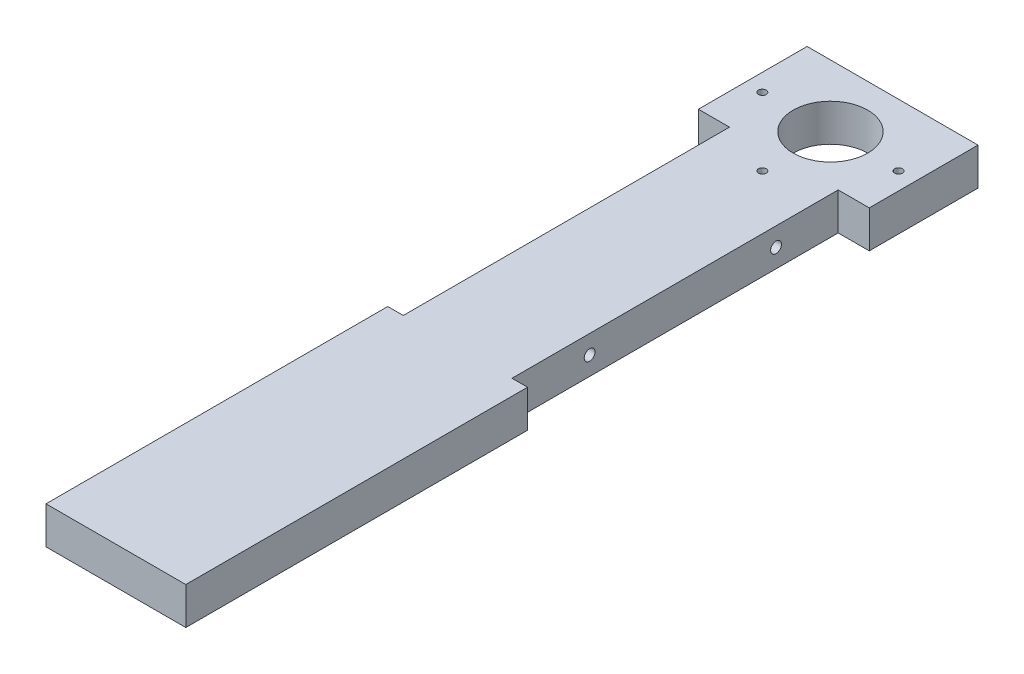
SolidWorks part; units mm, degrees
ref_plane "Front Plane" through (0, 0, 0) normal (0, 0, 1) x (1, 0, 0)
ref_plane "Top Plane" through (0, 0, 0) normal (0, 1, 0) x (1, 0, 0)
ref_plane "Right Plane" through (0, 0, 0) normal (1, 0, 0) x (0, 0, -1)
sketch "Sketch1" plane through (0, 0, 0) normal (0, 1, 0) x (1, 0, 0)
  line L1 (-22.5, 125) -> (22.5, 125)
  line L2 (-22.5, 125) -> (-22.5, -125)
  line L3 (-22.5, -125) -> (22.5, -125)
  line L4 (22.5, 125) -> (22.5, -125)
  line L5 (-22.5, 125) -> (22.5, -125) construction
  line L6 (-22.5, -125) -> (22.5, 125) construction
  point P0 (0, 0)
  dimension "D1" = 250
  dimension "D2" = 45
extrude "Boss-Extrude1" add sketch "Sketch1" along normal blind 12
sketch "Sketch2" plane through (0, 12, 0) normal (0, 1, 0) x (1, 0, 0)
  line L0 (22.5, 125) -> (22.5, 90) construction
  line L1 (22.5, -125) -> (22.5, 125) construction
  line L2 (0, -6.6) -> (0, 6.6) construction
  line L3 (22.5, 90) -> (17.5, 90)
  line L4 (22.5, 90) -> (22.5, -15)
  line L5 (22.5, -15) -> (17.5, -15)
  line L6 (17.5, 90) -> (17.5, -15)
  line L7 (-22.5, -15) -> (-17.5, -15)
  line L8 (-17.5, 90) -> (-17.5, -15)
  line L9 (-22.5, 90) -> (-17.5, 90)
  line L10 (-22.5, 90) -> (-22.5, -15)
  dimension "D2" = 105
  dimension "D1" = 35
  dimension "D3" = 5
extrude "Cut-Extrude1" cut sketch "Sketch2" against normal blind 12
sketch "Sketch3" plane through (17.5, 0, 0) normal (1, 0, 0) x (0, 0, -1)
  line L0 (90, 6) -> (70, 6) construction
  line L1 (90, 0) -> (90, 12) construction
  line L2 (70, 6) -> (10, 6) construction
  circle A0 centre (10, 6) radius 1.75
  circle A1 centre (70, 6) radius 1.75
  dimension "D3" = 3.5
  dimension "D4" = 3.5
  dimension "D1" = 20
  dimension "D2" = 60
extrude "Cut-Extrude2" cut sketch "Sketch3" against normal blind 35
sketch "Sketch5" plane through (0, 12, 0) normal (0, 1, 0) x (1, 0, 0)
  line L1 (22.5, 125) -> (27.5, 125)
  line L2 (22.5, 125) -> (22.5, 90)
  line L3 (22.5, 90) -> (27.5, 90)
  line L4 (27.5, 125) -> (27.5, 90)
  line L5 (-22.5, 125) -> (-27.5, 125)
  line L6 (-22.5, 125) -> (-22.5, 90)
  line L7 (-22.5, 90) -> (-27.5, 90)
  line L8 (-27.5, 125) -> (-27.5, 90)
  dimension "D1" = 35
  dimension "D2" = 5
  dimension "D3" = 35
  dimension "D4" = 5
extrude "Boss-Extrude2" add sketch "Sketch5" against normal up to surface (12 mm away) up to face at (0, 0, -25)
sketch "Sketch7" plane through (0, 12, 0) normal (0, 1, 0) x (1, 0, 0)
  line L0 (0, 125) -> (0, 105) construction
  line L1 (27.5, 125) -> (-27.5, 125) construction
  line L3 (0, 83.0797) -> (21.9203, 105) construction
  line L4 (21.9203, 105) -> (0, 126.9203) construction
  line L5 (0, 126.9203) -> (-21.9203, 105) construction
  line L6 (-21.9203, 105) -> (0, 83.0797) construction
  circle A0 centre (0, 105) radius 12
  circle A1 centre (0, 105) radius 15.5 construction
  circle A2 centre (21.9203, 105) radius 1.25
  circle A3 centre (-21.9203, 105) radius 1.25
  circle A4 centre (0, 83.0797) radius 1.25
  dimension "D2" = 24
  dimension "D3" = 2.5
  dimension "D4" = 2.5
  dimension "D5" = 2.5
  dimension "D1" = 20
extrude "Cut-Extrude3" cut sketch "Sketch7" against normal blind 35
